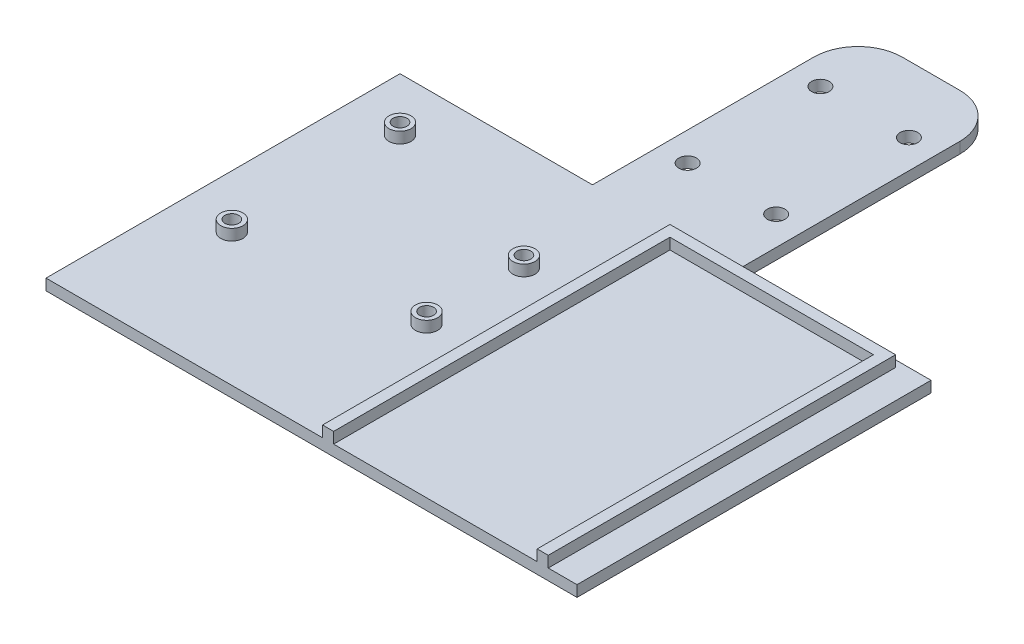
SolidWorks part; units mm, degrees
ref_plane "Front Plane" through (0, 0, 0) normal (0, 0, 1) x (1, 0, 0)
ref_plane "Top Plane" through (0, 0, 0) normal (0, 1, 0) x (1, 0, 0)
ref_plane "Right Plane" through (0, 0, 0) normal (1, 0, 0) x (0, 0, -1)
sketch "Sketch1" plane through (0, 0, 0) normal (0, 1, 0) x (1, 0, 0)
  line L1 (-20.955, -38.1) -> (20.955, -38.1)
  line L2 (-20.955, -38.1) -> (-20.955, 38.1)
  line L3 (-20.955, 38.1) -> (20.955, 38.1)
  line L4 (20.955, -38.1) -> (20.955, 38.1)
  line L5 (-20.955, -38.1) -> (20.955, 38.1) construction
  line L6 (-20.955, 38.1) -> (20.955, -38.1) construction
  line L7 (-12.7, -19.05) -> (12.7, -19.05) construction
  line L8 (-12.7, -19.05) -> (-12.7, 19.05) construction
  line L9 (-12.7, 19.05) -> (12.7, 19.05) construction
  line L10 (12.7, -19.05) -> (12.7, 19.05) construction
  line L11 (-12.7, -19.05) -> (12.7, 19.05) construction
  line L12 (-12.7, 19.05) -> (12.7, -19.05) construction
  circle A0 centre (-12.7, 19.05) radius 2.54
  circle A1 centre (-12.7, -19.05) radius 2.54
  circle A2 centre (12.7, -19.05) radius 2.54
  circle A3 centre (12.7, 19.05) radius 2.54
  point P0 (0, 0)
  point P5 (0, 0)
  dimension "D1" = 38.1
  dimension "D5" = 5.08
  dimension "D2" = 25.4
  dimension "D3" = 41.91
  dimension "D4" = 76.2
extrude "Boss-Extrude1" add sketch "Sketch1" along normal blind 3.175
sketch "Sketch2" plane through (0, 3.175, 0) normal (0, 1, 0) x (1, 0, 0)
  line L0 (-20.955, -38.1) -> (20.955, -38.1) construction
  line L1 (-76.2, -139.7) -> (76.2, -139.7)
  line L2 (-76.2, -139.7) -> (-76.2, -38.1)
  line L3 (-76.2, -38.1) -> (76.2, -38.1)
  line L4 (76.2, -139.7) -> (76.2, -38.1)
  line L5 (-76.2, -139.7) -> (76.2, -38.1) construction
  line L6 (-76.2, -38.1) -> (76.2, -139.7) construction
  point P0 (0, -88.9)
  dimension "D1" = 152.4
  dimension "D2" = 101.6
extrude "Boss-Extrude2" add sketch "Sketch2" against normal up to surface (3.175 mm away) up to face at (12.7, 0, 21.59)
sketch "Sketch3" plane through (0, 3.175, 0) normal (0, 1, 0) x (1, 0, 0)
  line L0 (-20.955, -38.1) -> (-76.2, -38.1) construction
  line L1 (-76.2, -101.6) -> (-10.16, -101.6) construction
  line L12 (-76.2, -101.6) -> (-76.2, -50.8) construction
  line L13 (-76.2, -50.8) -> (-10.16, -50.8) construction
  line L14 (-10.16, -101.6) -> (-10.16, -50.8) construction
  line L15 (-76.2, -101.6) -> (-10.16, -50.8) construction
  line L16 (-76.2, -50.8) -> (-10.16, -101.6) construction
  line L18 (-76.2, -38.1) -> (-76.2, -139.7) construction
  circle A0 centre (-60.96, -53.34) radius 2
  circle A1 centre (-60.96, -101.6) radius 2
  circle A2 centre (-10.16, -68.58) radius 2
  circle A3 centre (-10.16, -96.52) radius 2
  point P0 (-43.18, -76.2)
  point P13 (-60.6915, -76.3435)
  dimension "D3" = 15.24
  dimension "D5" = 17.78
  dimension "D7" = 4
  dimension "D1" = 50.8
  dimension "D2" = 66.04
  dimension "D4" = 2.54
  dimension "D6" = 45.72
  dimension "D8" = 12.7
extrude "Cut-Extrude1" cut sketch "Sketch3" against normal through all
sketch "Sketch4" plane through (0, 3.175, 0) normal (0, 1, 0) x (1, 0, 0)
  line L0 (76.2, -139.7) -> (76.2, -38.1) construction
  line L1 (7.62, -44.45) -> (63.5, -44.45) construction
  line L2 (7.62, -44.45) -> (7.62, -120.65) construction
  line L3 (7.62, -120.65) -> (63.5, -120.65) construction
  line L4 (63.5, -44.45) -> (63.5, -120.65) construction
  line L5 (7.62, -44.45) -> (63.5, -120.65) construction
  line L6 (7.62, -120.65) -> (63.5, -44.45) construction
  line L7 (76.2, -38.1) -> (20.955, -38.1) construction
  line L8 (64.77, -43.18) -> (64.77, -120.65)
  line L9 (6.35, -43.18) -> (64.77, -43.18)
  line L10 (6.35, -43.18) -> (6.35, -120.65)
  line L11 (67.945, -40.005) -> (67.945, -120.65)
  line L12 (3.175, -40.005) -> (67.945, -40.005)
  line L13 (3.175, -40.005) -> (3.175, -120.65)
  line L14 (3.175, -120.65) -> (3.175, -139.7)
  line L15 (-76.2, -139.7) -> (76.2, -139.7) construction
  line L16 (3.175, -139.7) -> (6.35, -139.7)
  line L17 (6.35, -139.7) -> (6.35, -120.65)
  line L18 (64.77, -120.65) -> (64.77, -139.7)
  line L19 (64.77, -139.7) -> (67.945, -139.7)
  line L20 (67.945, -139.7) -> (67.945, -120.65)
  point P0 (35.56, -82.55)
  dimension "D1" = 55.88
  dimension "D2" = 76.2
  dimension "D3" = 12.7
  dimension "D4" = 6.35
  dimension "D5" = 1.27
  dimension "D6" = 3.175
extrude "Boss-Extrude3" add sketch "Sketch4" along normal blind 3.175
sketch "Sketch5" plane through (0, 3.175, 0) normal (0, 1, 0) x (1, 0, 0)
  circle A0 centre (-60.96, -53.34) radius 2
  circle A1 centre (-60.96, -53.34) radius 3.175
  circle A2 centre (-60.96, -101.6) radius 2
  circle A3 centre (-60.96, -101.6) radius 3.175
  circle A4 centre (-10.16, -96.52) radius 2
  circle A5 centre (-10.16, -96.52) radius 3.175
  circle A6 centre (-10.16, -68.58) radius 3.175
  circle A7 centre (-10.16, -68.58) radius 2
  circle A8 centre (-60.96, -53.34) radius 2 construction
  dimension "D1" = 6.35
extrude "Boss-Extrude4" add sketch "Sketch5" along normal blind 3.175
fillet "Fillet1" radius 12.7 2 edges at (-20.955, 1.5875, -38.1) (20.955, 1.5875, -38.1)
